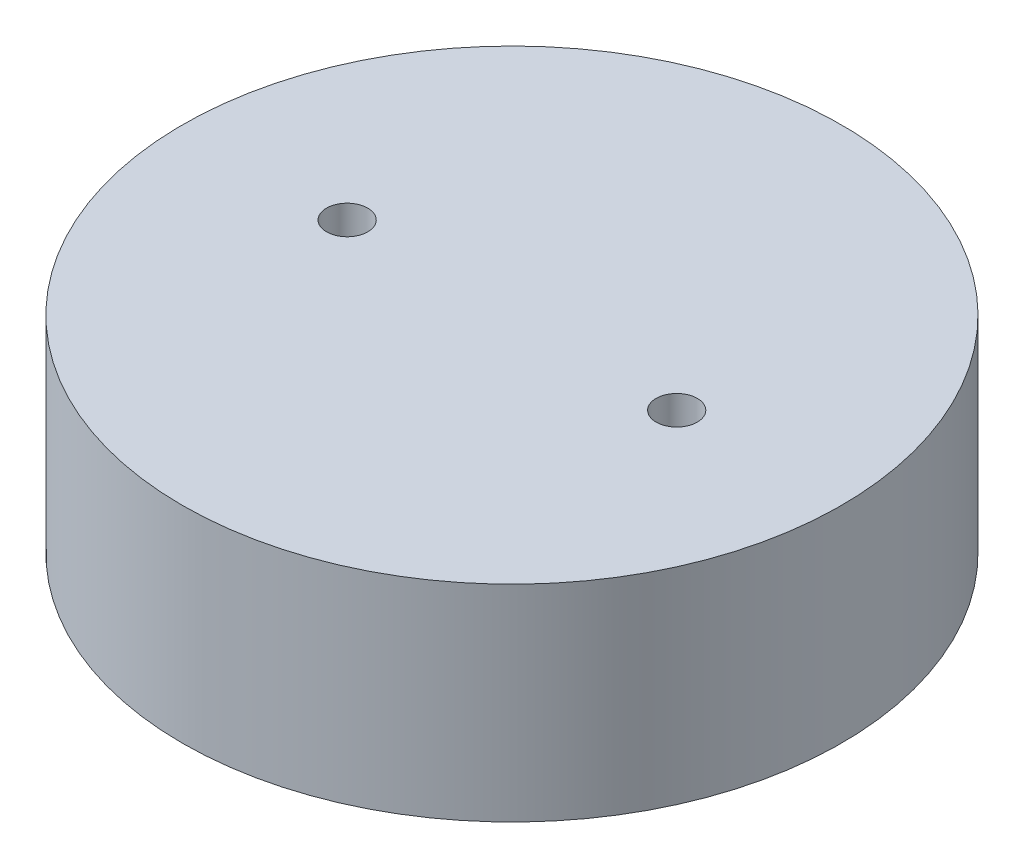
SolidWorks part; units mm, degrees
ref_plane "Front Plane" through (0, 0, 0) normal (0, 0, 1) x (1, 0, 0)
ref_plane "Top Plane" through (0, 0, 0) normal (0, 1, 0) x (1, 0, 0)
ref_plane "Right Plane" through (0, 0, 0) normal (1, 0, 0) x (0, 0, -1)
sketch "Sketch1" plane through (0, 0, 0) normal (0, 1, 0) x (1, 0, 0)
  line L1 (29, 13.1285) -> (-29, 13.1285) construction
  line L2 (29, 13.1285) -> (29, -13.1285) construction
  line L3 (29, -13.1285) -> (-29, -13.1285) construction
  line L4 (-29, 13.1285) -> (-29, -13.1285) construction
  line L5 (29, 13.1285) -> (-29, -13.1285) construction
  line L6 (29, -13.1285) -> (-29, 13.1285) construction
  circle A0 centre (0, 0) radius 40
  circle A1 centre (-20, 0) radius 2.5
  circle A2 centre (20, 0) radius 2.5
  dimension "D1" = 80
  dimension "D2" = 5
  dimension "D3" = 5
  dimension "D4" = 20
  dimension "D5" = 20
  dimension "D6" = 58
extrude "Boss-Extrude1" add sketch "Sketch1" against normal blind 25
